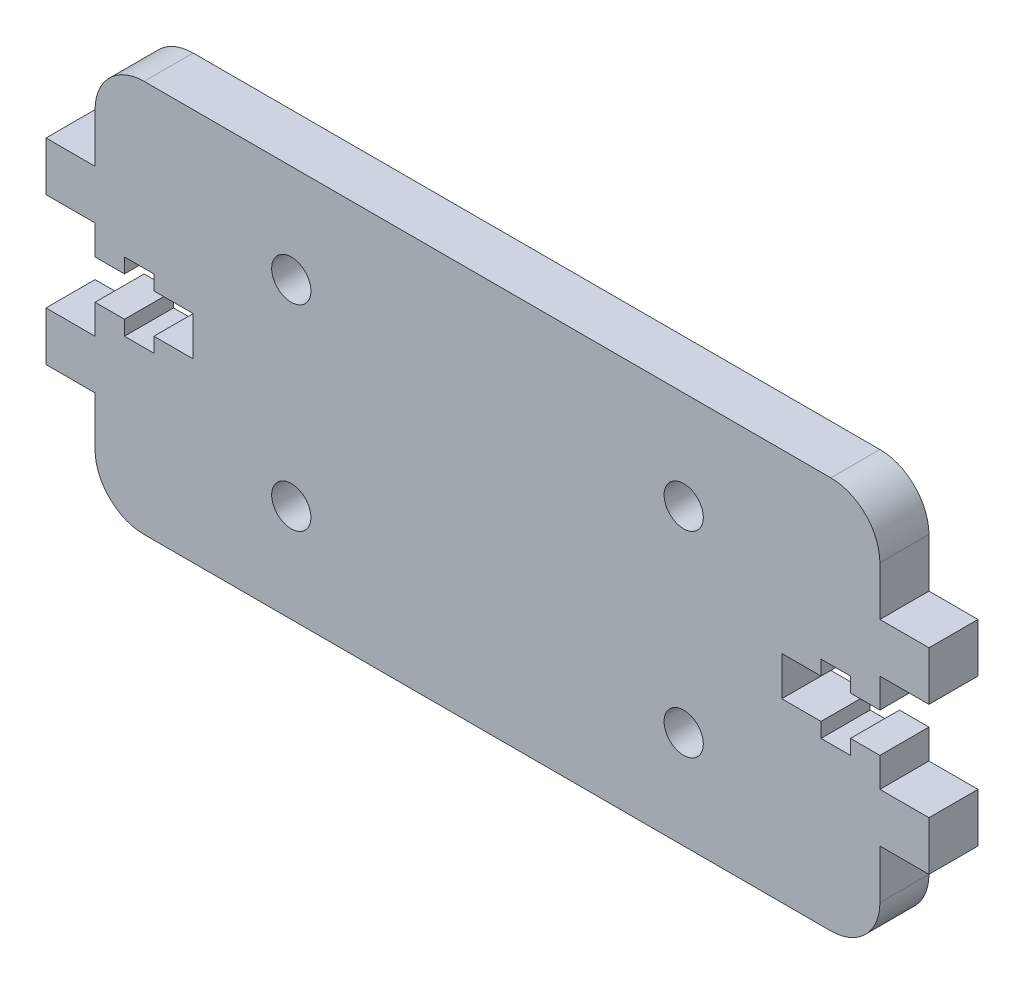
SolidWorks part; units mm, degrees
ref_plane "Plan de face" through (0, 0, 0) normal (0, 0, 1) x (1, 0, 0)
ref_plane "Plan de dessus" through (0, 0, 0) normal (0, 1, 0) x (1, 0, 0)
ref_plane "Plan de droite" through (0, 0, 0) normal (1, 0, 0) x (0, 0, -1)
sketch "Esquisse1" plane through (0, 0, 0) normal (0, 0, 1) x (1, 0, 0)
  line L0 (-40, 0) -> (40, 0)
  line L1 (2.5, 20) -> (40, 20) construction
  line L2 (-40, 30) -> (-40, 40)
  line L3 (0, 62.4131) -> (0, -5.9928) construction
  line L4 (-40, 10) -> (-40, 0)
  line L9 (-40, 40) -> (40, 40)
  line L24 (40, 30) -> (40, 40)
  line L44 (40, 0) -> (40, 10)
  circle A0 centre (20, 30) radius 2
  circle A1 centre (-20, 30) radius 2
  circle A2 centre (-20, 10) radius 2
  circle A3 centre (20, 10) radius 2
  point P8 (0, 40)
  point P26 (0, 0)
  line B0 (-37, 23.5) -> (-34, 23.5)
  line B1 (-34, 18) -> (-30, 18)
  line B2 (-30, 22) -> (-34, 22)
  line B3 (-34, 23.5) -> (-34, 22)
  line B4 (-40, 20) -> (-28.7792, 20) construction
  line B5 (-40, 22) -> (-40, 25)
  line B6 (-45, 25) -> (-45, 30)
  line B7 (-45, 30) -> (-40, 30)
  line B8 (-45, 25) -> (-40, 25)
  line B9 (-40, 18) -> (-40, 15)
  line B10 (-40, 15) -> (-45, 15)
  line B11 (-45, 15) -> (-45, 10)
  line B12 (-45, 10) -> (-40, 10)
  line B13 (-40, 22) -> (-40, 18) construction
  line B14 (-40, 18) -> (-37, 18)
  line B15 (-34, 18) -> (-34, 16.5)
  line B16 (-37, 16.5) -> (-37, 18)
  line B17 (-30, 18) -> (-30, 22)
  line B18 (-37, 22) -> (-37, 23.5)
  line B19 (-34, 16.5) -> (-37, 16.5)
  line B20 (-37, 22) -> (-40, 22)
  line B21 (-30, 20) -> (-40, 20) construction
  line B22 (37, 23.5) -> (34, 23.5)
  line B23 (34, 18) -> (30, 18)
  line B24 (30, 22) -> (34, 22)
  line B25 (34, 23.5) -> (34, 22)
  line B26 (40, 20) -> (28.7792, 20) construction
  line B27 (40, 22) -> (40, 25)
  line B28 (45, 25) -> (45, 30)
  line B29 (45, 30) -> (40, 30)
  line B30 (45, 25) -> (40, 25)
  line B31 (40, 18) -> (40, 15)
  line B32 (40, 15) -> (45, 15)
  line B33 (45, 15) -> (45, 10)
  line B34 (45, 10) -> (40, 10)
  line B35 (40, 22) -> (40, 18) construction
  line B36 (40, 18) -> (37, 18)
  line B37 (34, 18) -> (34, 16.5)
  line B38 (37, 16.5) -> (37, 18)
  line B39 (30, 18) -> (30, 22)
  line B40 (37, 22) -> (37, 23.5)
  line B41 (34, 16.5) -> (37, 16.5)
  line B42 (37, 22) -> (40, 22)
  line B43 (30, 20) -> (40, 20) construction
  dimension "D10" = 4
  dimension "D1" = 40
  dimension "D2" = 80
  dimension "D11" = 40
  dimension "D12" = 20
sketch_block_instance "Insert M4 plots ep 5mm-1"
sketch_block "Insert M4 plots ep 5mm" parameters "D1"=10, "D2"=5, "D3"=5, "D4"=7, "D5"=4, "D6"=3, "D7"=3, "D8"=10
sketch_block_instance "Insert M4 plots ep 5mm-3"
extrude "Boss.-Extru.1" add sketch "Esquisse1" along normal blind 5 contours B40 B42 B27 B30 B28 B29 L24 L9 L2 B7 B6 B8 B5 B20 B18 B0 B3 B2 B17 B1 B15 B19 B16 B14 B9 B10 B11 B12 L4 L0 L44 B34 B33 B32 B31 B36 B38 B41 B37 B23 B39 B24 B25 B22 A0 A1 A2
fillet "Congé1" radius 5 4 edges at (40, 0, 2.5) (40, 40, 2.5) (-40, 0, 2.5) (-40, 40, 2.5)
